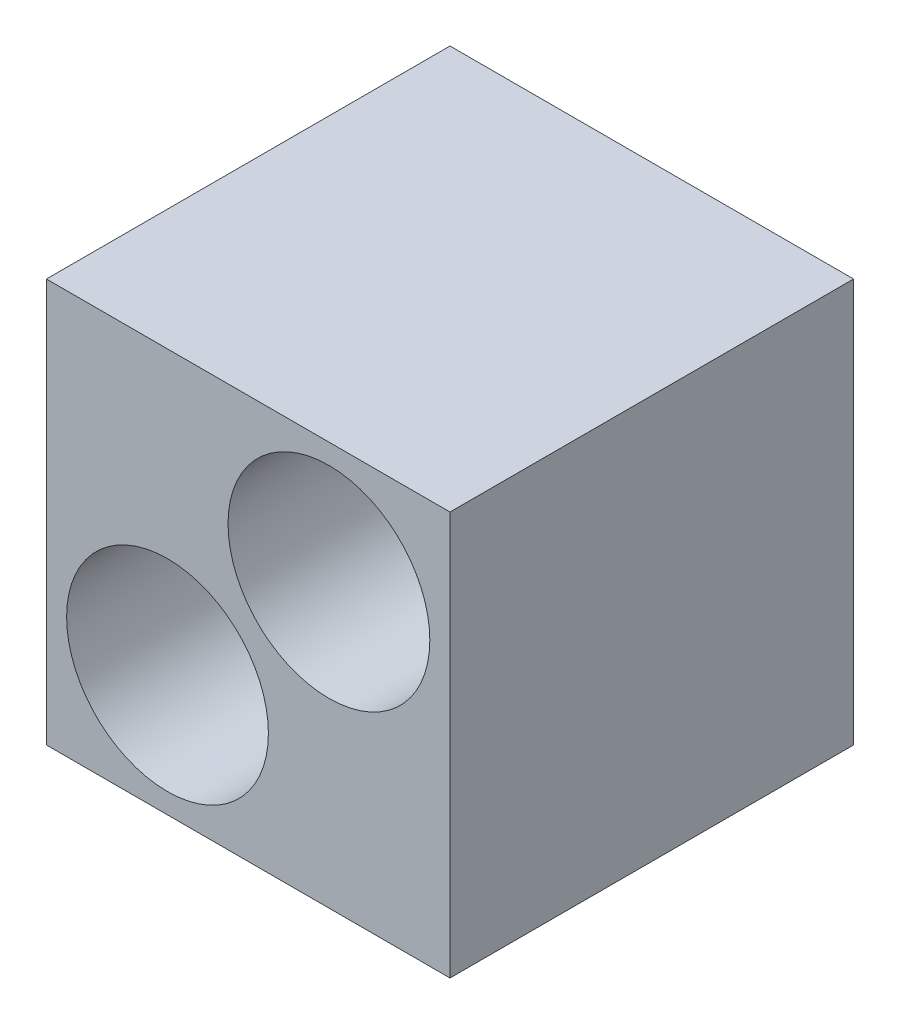
SolidWorks part; units mm, degrees
ref_plane "Front Plane" through (0, 0, 0) normal (0, 0, 1) x (1, 0, 0)
ref_plane "Top Plane" through (0, 0, 0) normal (0, 1, 0) x (1, 0, 0)
ref_plane "Right Plane" through (0, 0, 0) normal (1, 0, 0) x (0, 0, -1)
sketch "Sketch1" plane through (0, 0, 0) normal (0, 0, 1) x (1, 0, 0)
  line L1 (0, 0) -> (10, 0)
  line L2 (0, 0) -> (0, 10)
  line L3 (0, 10) -> (10, 10)
  line L4 (10, 0) -> (10, 10)
extrude "Boss-Extrude1" add sketch "Sketch1" along normal blind 10
sketch "Sketch2" plane through (0, 0, 0) normal (0, 0, 1) x (1, 0, 0)
  circle A0 centre (3, 3) radius 2.5
  circle A1 centre (7, 7) radius 2.5
extrude "Cut-Extrude2" cut sketch "Sketch2" along normal through all
